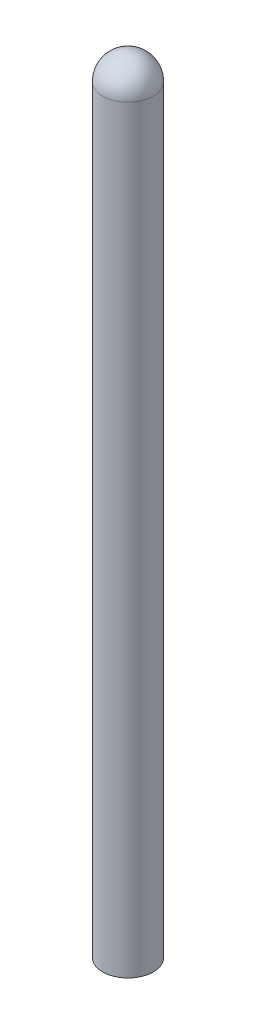
SolidWorks part; units mm, degrees
ref_plane "Ön Düzlem" through (0, 0, 0) normal (0, 0, 1) x (1, 0, 0)
ref_plane "Üst Düzlem" through (0, 0, 0) normal (0, 1, 0) x (1, 0, 0)
ref_plane "Sağ Düzlem" through (0, 0, 0) normal (1, 0, 0) x (0, 0, -1)
sketch "Çizim1" plane through (0, 0, 0) normal (0, 1, 0) x (1, 0, 0)
  circle A0 centre (0, 0) radius 5
  circle A1 centre (0, 0) radius 3
  dimension "D1" = 10
  dimension "D2" = 6
extrude "Yükseklik-Ekstrüzyon1" add sketch "Çizim1" along normal blind 150
sketch "Çizim2" plane through (0, 150, 0) normal (0, 1, 0) x (1, 0, 0)
  circle A0 centre (0, 0) radius 5
  dimension "D1" = 10
extrude "Yükseklik-Ekstrüzyon2" add sketch "Çizim2" along normal blind 5
fillet "Radyus1" radius 5 1 edges at (0, 155, 5)
